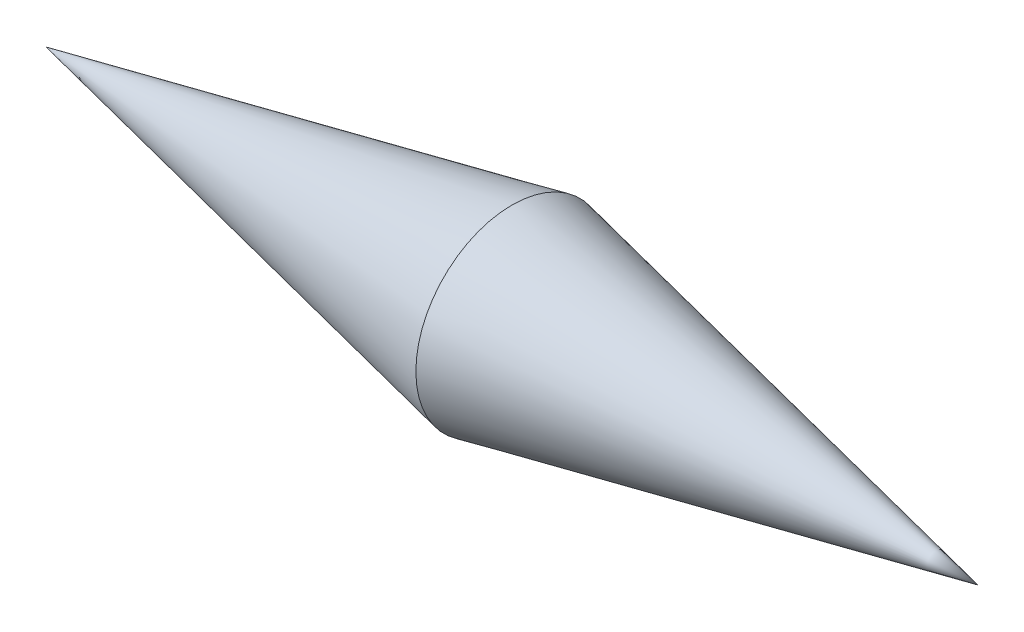
SolidWorks part; units mm, degrees
ref_plane "Front Plane" through (0, 0, 0) normal (0, 0, 1) x (1, 0, 0)
ref_plane "Top Plane" through (0, 0, 0) normal (0, 1, 0) x (1, 0, 0)
ref_plane "Right Plane" through (0, 0, 0) normal (1, 0, 0) x (0, 0, -1)
sketch "Sketch1" plane through (0, 0, 0) normal (0, 0, 1) x (1, 0, 0)
  line L0 (0, 0) -> (3.078, 0.635)
  line L1 (3.078, 0.635) -> (6.1561, 0)
  line L2 (6.1561, 0) -> (0, 0)
  dimension "D2" = 0.635
  dimension "D1" = 6.1561
revolve "Revolve1" add sketch "Sketch1" angle 360 about L2
ref_plane "Plane2" through (6.1561, 0, 0) normal (1, 0, 0) x (0, 0, -1)
sketch "Sketch3" plane through (6.1561, 0, 0) normal (1, 0, 0) x (0, 0, -1)
  line L0 (0, 0.635) -> (0, -0.635) construction
  line L1 (-0.635, 0) -> (0.635, 0) construction
  circle A0 centre (0, 0) radius 0.635 construction
sketch "Sketch4" plane through (0, 0, 0) normal (0, 1, 0) x (1, 0, 0)
  line L0 (6.1561, 0) -> (6.7911, 0) construction
  line L1 (6.1561, -0.635) -> (6.1561, 0.635) construction
  dimension "D1" = 0.635
equation "\"A0\" = 0.2423649291574499"
equation "\"A1\" = 0.2496592870602803"
equation "\"B0\" = 0.5591382141232927"
equation "\"B1\" = 0.5581666265579283"
equation "\"B2\" = 0.559393565791922"
equation "\"B3\" = 0.5582496337048435"
equation "\"B4\" = 0.5590195579140136"
equation "\"B5\" = 0.5589568805398694"
equation "\"C0\" = 0.9009843279267108"
equation "\"C1\" = 0.9028237285634917"
equation "\"C2\" = 0.9010889074062941"
equation "\"D0\" = 0.9241157610080546"
equation "\"D1\" = 0.924427510570291"
equation "\"D1@Sketch1\"=\"A0\""
